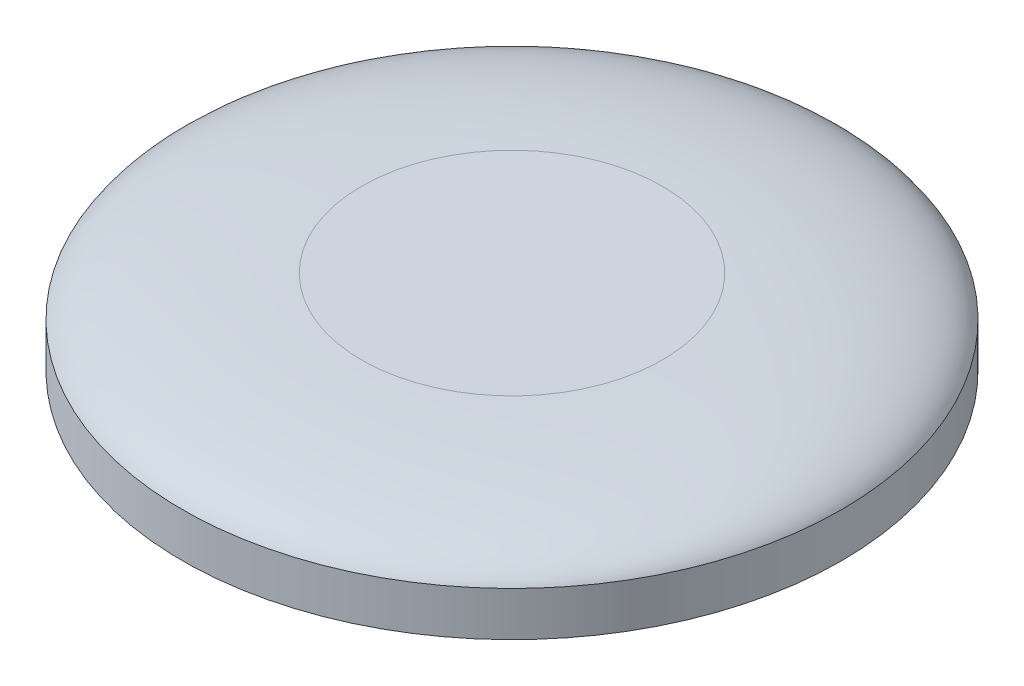
SolidWorks part; units mm, degrees
ref_plane "Plan de face" through (0, 0, 0) normal (0, 0, 1) x (1, 0, 0)
ref_plane "Plan de dessus" through (0, 0, 0) normal (0, 1, 0) x (1, 0, 0)
ref_plane "Plan de droite" through (0, 0, 0) normal (1, 0, 0) x (0, 0, -1)
sketch "Esquisse1" plane through (0, 0, 0) normal (0, 0, 1) x (1, 0, 0)
  line L0 (0, 0) -> (-11.4144, 0)
  line L1 (0, 0) -> (0, -1.5601)
  line L2 (-23, -6.405) -> (-23, -5.405)
  line L3 (-25, -6.405) -> (-23, -6.405)
  line L4 (-23, -5.405) -> (-23.5, -5.405)
  line L5 (0, -1.5601) -> (-13.517, -1.5601)
  line L6 (-23.5, -3.405) -> (-13.517, -1.5601)
  line L7 (-23.5, -3.405) -> (-23.5, -5.405)
  line L10 (-25, -6.405) -> (-25, -3.0432)
  spline S0 degree 2 poles (-11.4144, 0) (-23.4645, -0.3249) (-25, -3.0432) knots 0 0 0 1 1 1
  dimension "D1" = 25
  dimension "D2" = 23.5
  dimension "D3" = 2
  dimension "D4" = 1
revolve "Révolution1" add sketch "Esquisse1" angle 360 about L1
